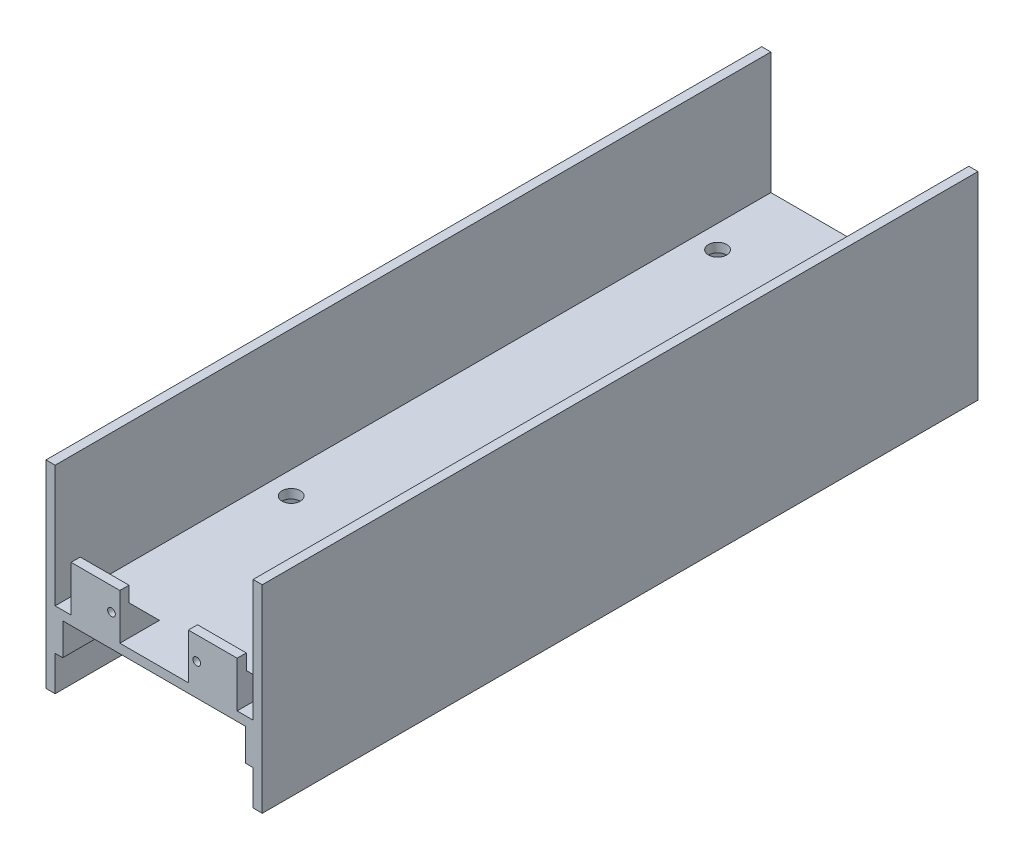
SolidWorks part; units mm, degrees
ref_plane "Front Plane" through (0, 0, 0) normal (0, 0, 1) x (1, 0, 0)
ref_plane "Top Plane" through (0, 0, 0) normal (0, 1, 0) x (1, 0, 0)
ref_plane "Right Plane" through (0, 0, 0) normal (1, 0, 0) x (0, 0, -1)
sketch "Sketch1" plane through (0, 0, 0) normal (0, 0, 1) x (1, 0, 0)
  line L0 (0, 0) -> (0, 32.2637) construction
  line L1 (-32.5, 13) -> (-32.5, 1.5)
  line L2 (-32.5, 1.5) -> (-35.5, 1.5)
  line L3 (-35.5, 1.5) -> (-35.5, 26.5)
  line L4 (-32.5, 26.5) -> (32.5, 26.5)
  line L5 (-29, 23) -> (29, 23) construction
  line L6 (-32, 13) -> (-32, -11) construction
  line L7 (-30, 23.5) -> (30, 23.5)
  line L8 (35.5, 1.5) -> (35.5, 26.5)
  line L9 (32.5, 1.5) -> (35.5, 1.5)
  line L10 (32.5, 13) -> (32.5, 1.5)
  line L11 (-32.5, 13) -> (-30, 13)
  line L12 (-30, 13) -> (-30, 23.5)
  line L13 (-30, 13) -> (-32, 13) construction
  line L14 (-32.5, 23.5) -> (-32.5, 13) construction
  line L15 (-32.5, 23.5) -> (-30, 23.5) construction
  line L16 (32.5, 13) -> (30, 13)
  line L17 (30, 13) -> (30, 23.5)
  line L18 (30, 23.5) -> (32.5, 23.5) construction
  line L19 (32.5, 23.5) -> (32.5, 13) construction
  line L20 (-35.5, 26.5) -> (-35.5, 66.5)
  line L21 (-35.5, 66.5) -> (-32.5, 66.5)
  line L22 (-32.5, 66.5) -> (-32.5, 26.5)
  line L23 (35.5, 66.5) -> (32.5, 66.5)
  line L24 (35.5, 26.5) -> (35.5, 66.5)
  line L25 (32.5, 66.5) -> (32.5, 26.5)
  line L26 (-35.5, 26.5) -> (-32.5, 26.5) construction
  line L27 (32.5, 26.5) -> (35.5, 26.5) construction
  point P13 (0, 23.5)
  point P15 (0, 26.5)
  dimension "D1" = 3
  dimension "D2" = 25
  dimension "D3" = 0.5
  dimension "D4" = 0.5
  dimension "D5" = 3
  dimension "D6" = 40
extrude "Boss-Extrude1" add sketch "Sketch1" against normal blind 153 and the other way blind 82
sketch "Sketch2" plane through (0, 26.5, 0) normal (0, 1, 0) x (1, 0, 0)
  line L0 (0, 0) -> (0, 108.9013) construction
  line L1 (32.5, 153) -> (-32.5, 153) construction
  line L2 (25, -12) -> (-25, -12) construction
  line L3 (25, -12) -> (25, 128) construction
  line L4 (25, 128) -> (-25, 128) construction
  line L5 (-25, -12) -> (-25, 128) construction
  line L6 (25, -12) -> (-25, 128) construction
  line L7 (25, 128) -> (-25, -12) construction
  circle A0 centre (-25, 128) radius 3
  circle A1 centre (25, 128) radius 3
  circle A2 centre (25, -12) radius 3
  circle A3 centre (-25, -12) radius 3
  circle A4 centre (-25, 128) radius 1.4 construction
  circle A5 centre (25, 128) radius 1.4 construction
  circle A6 centre (25, -12) radius 1.4 construction
  circle A7 centre (-25, -12) radius 1.4 construction
  point P3 (0, 58)
  dimension "D3" = 6
  dimension "D4" = 6
  dimension "D5" = 6
  dimension "D6" = 6
  dimension "D8" = 2.8
  dimension "D9" = 2.8
  dimension "D10" = 2.8
  dimension "D11" = 2.8
  dimension "D1" = 140
  dimension "D2" = 50
  dimension "D7" = 25
sketch "Sketch3" plane through (0, 26.5, 0) normal (0, 1, 0) x (1, 0, 0)
  line L0 (0, 0) -> (0, -117.0063) construction
  line L1 (-27.25, -82) -> (-11.25, -82)
  line L2 (-11.25, -82) -> (-11.25, -79)
  line L3 (-11.25, -79) -> (-27.25, -79)
  line L4 (-27.25, -79) -> (-27.25, -82)
  line L5 (11.25, -79) -> (27.25, -79)
  line L6 (11.25, -82) -> (11.25, -79)
  line L7 (27.25, -82) -> (11.25, -82)
  line L8 (27.25, -79) -> (27.25, -82)
  line L9 (32.5, -82) -> (-32.5, -82) construction
  dimension "D1" = 22.5
  dimension "D2" = 16
  dimension "D3" = 3
  dimension "D4" = 0
extrude "Boss-Extrude3" add sketch "Sketch3" along normal blind 15
chamfer "Chamfer1" distance 10 angle 45 2 edges at (19.25, 26.5, 79) (-19.25, 26.5, 79)
sketch "Sketch4" plane through (0, 0, 82) normal (0, 0, 1) x (1, 0, 0)
  circle A0 centre (-14, 33.95) radius 1.25
  circle A1 centre (14, 33.95) radius 1.25
  dimension "D1" = 2.5
  dimension "D2" = 2.5
extrude "Cut-Extrude1" cut sketch "Sketch4" against normal blind 10
extrude "Cut-Extrude2" cut sketch "Sketch2" against normal blind 10
